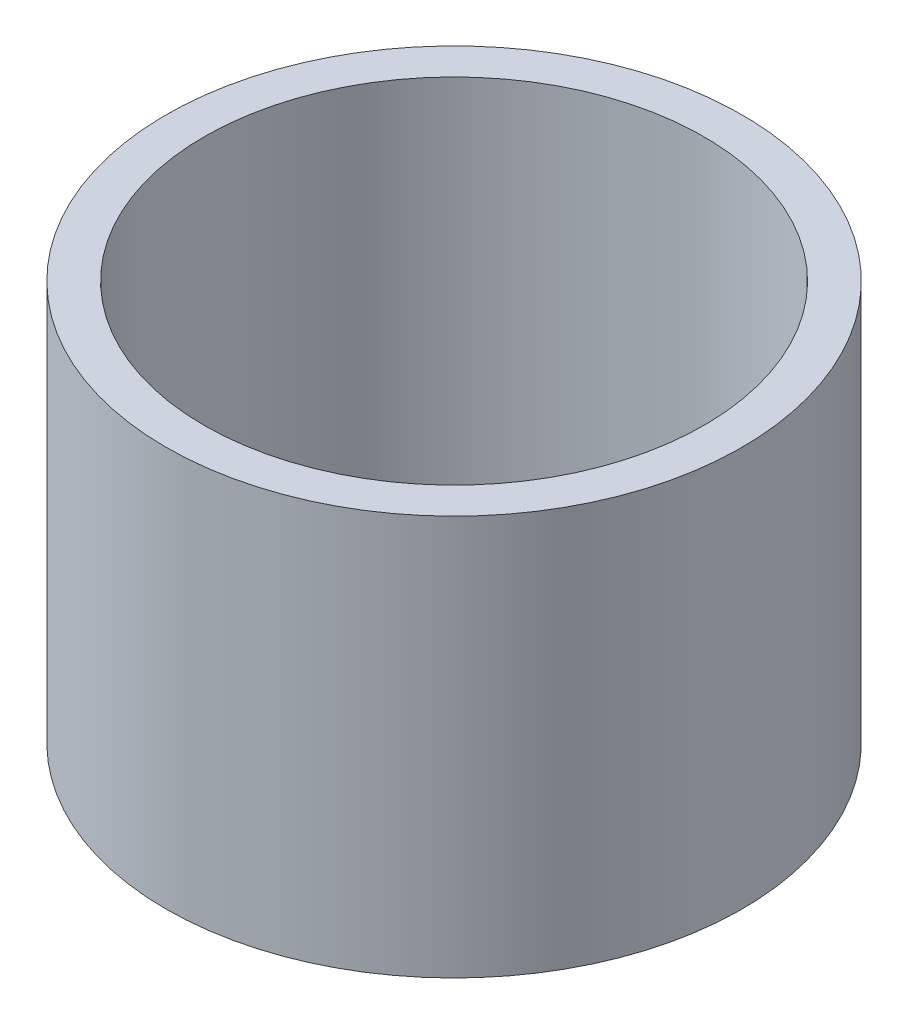
SolidWorks part; units mm, degrees
ref_plane "Front Plane" through (0, 0, 0) normal (0, 0, 1) x (1, 0, 0)
ref_plane "Top Plane" through (0, 0, 0) normal (0, 1, 0) x (1, 0, 0)
ref_plane "Right Plane" through (0, 0, 0) normal (1, 0, 0) x (0, 0, -1)
sketch "Sketch1" plane through (0, 0, 0) normal (0, 1, 0) x (1, 0, 0)
  circle A0 centre (0, 0) radius 3.6
extrude "Boss-Extrude1" add sketch "Sketch1" along normal blind 5
sketch "Sketch2" plane through (0, 5, 0) normal (0, 1, 0) x (1, 0, 0)
  circle A0 centre (0, 0) radius 3.125
extrude "Cut-Extrude1" cut sketch "Sketch2" against normal blind 4.5
